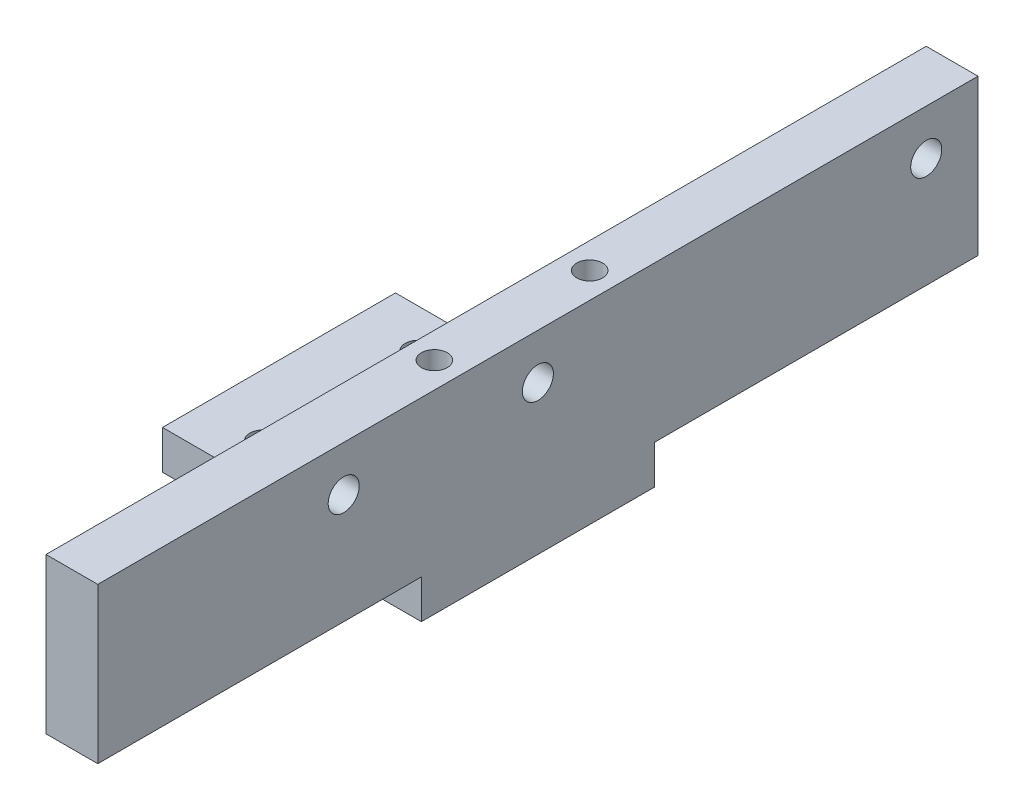
SolidWorks part; units mm, degrees
ref_plane "前视基准面" through (0, 0, 0) normal (0, 0, 1) x (1, 0, 0)
ref_plane "上视基准面" through (0, 0, 0) normal (0, 1, 0) x (1, 0, 0)
ref_plane "右视基准面" through (0, 0, 0) normal (1, 0, 0) x (0, 0, -1)
other "Configuration Table"
sketch "草图1" plane through (0, 0, 0) normal (0, 1, 0) x (1, 0, 0)
  line L0 (5, 0) -> (25, 0)
  line L5 (5, -18) -> (5, 0)
  line L6 (25, 0) -> (25, -18)
  line L12 (5, -18) -> (25, -18)
  dimension "D3" = 18
  dimension "D1" = 18
  dimension "D5" = 20
extrude "凸台-拉伸1" add sketch "草图1" along normal blind 3 contours L5 L0 L6 L12
sketch "草图2" plane through (0, 3, 0) normal (0, 1, 0) x (1, 0, 0)
  line L0 (5, -18) -> (25, -18) construction
  line L1 (25, 0) -> (21, 0)
  line L2 (25, 0) -> (25, -18)
  line L3 (25, -18) -> (21, -18)
  line L4 (21, 0) -> (21, -18)
  dimension "D1" = 4
extrude "凸台-拉伸2" add sketch "草图2" along normal blind 12
sketch "草图4" plane through (0, 0, 0) normal (0, -1, 0) x (1, 0, 0)
  circle A0 centre (17.75, 15) radius 1
  circle A1 centre (17.75, 3) radius 1
  circle A2 centre (9.75, 3) radius 1
  circle A3 centre (9.75, 15) radius 1
  dimension "D1" = 2
  dimension "D2" = 2
  dimension "D3" = 2
  dimension "D4" = 2
extrude "切除-拉伸1" cut sketch "草图4" against normal through all
sketch "草图5" plane through (0, 15, 0) normal (0, 1, 0) x (1, 0, 0)
  line L0 (21, 0) -> (21, -18) construction
  line L1 (5, 0) -> (21, 0) construction
  circle A0 centre (23, -15) radius 1
  circle A1 centre (23, -3) radius 1
  dimension "D1" = 2
  dimension "D2" = 2
  dimension "D3" = 12
  dimension "D4" = 2
  dimension "D5" = 2
  dimension "D6" = 3
extrude "切除-拉伸2" cut sketch "草图5" against normal blind 5
sketch "草图6" plane through (0, 0, 18) normal (0, 0, 1) x (1, 0, 0)
  line L1 (25, 15) -> (21, 15)
  line L2 (25, 15) -> (25, 3)
  line L3 (25, 3) -> (21, 3)
  line L4 (21, 15) -> (21, 3)
extrude "凸台-拉伸3" add sketch "草图6" along normal blind 25
sketch "草图7" plane through (0, 0, 0) normal (0, 0, -1) x (-1, 0, 0)
  line L1 (-25, 15) -> (-21, 15)
  line L2 (-25, 15) -> (-25, 3)
  line L3 (-25, 3) -> (-21, 3)
  line L4 (-21, 15) -> (-21, 3)
extrude "凸台-拉伸4" add sketch "草图7" along normal blind 25
sketch "草图8" plane through (21, 0, 0) normal (-1, 0, 0) x (0, 0, 1)
  circle A0 centre (-36, 11.5) radius 1.2
  circle A1 centre (-21, 11.5) radius 1.2
  circle A3 centre (9, 11.5) radius 1.2
  circle A4 centre (24, 11.5) radius 1.2
extrude "切除-拉伸3" cut sketch "草图8" against normal up to surface (4 mm away) up to face at (25, 5.25, 9)
